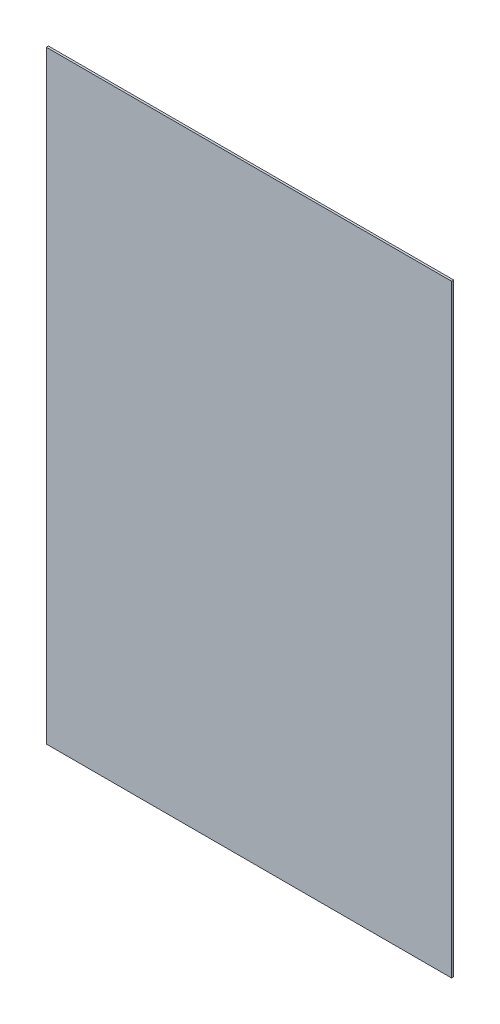
SolidWorks part; units mm, degrees
ref_plane "Front Plane" through (0, 0, 0) normal (0, 0, 1) x (1, 0, 0)
ref_plane "Top Plane" through (0, 0, 0) normal (0, 1, 0) x (1, 0, 0)
ref_plane "Right Plane" through (0, 0, 0) normal (1, 0, 0) x (0, 0, -1)
sketch "Sketch1" plane through (0, 0, 0) normal (0, 0, 1) x (1, 0, 0)
  line L1 (-113.49, 9.5) -> (113.49, 9.5)
  line L2 (-113.49, 9.5) -> (-113.49, -328.5)
  line L3 (-113.49, -328.5) -> (113.49, -328.5)
  line L4 (113.49, 9.5) -> (113.49, -328.5)
extrude "Boss-Extrude1" add sketch "Sketch1" along normal blind 1.2
